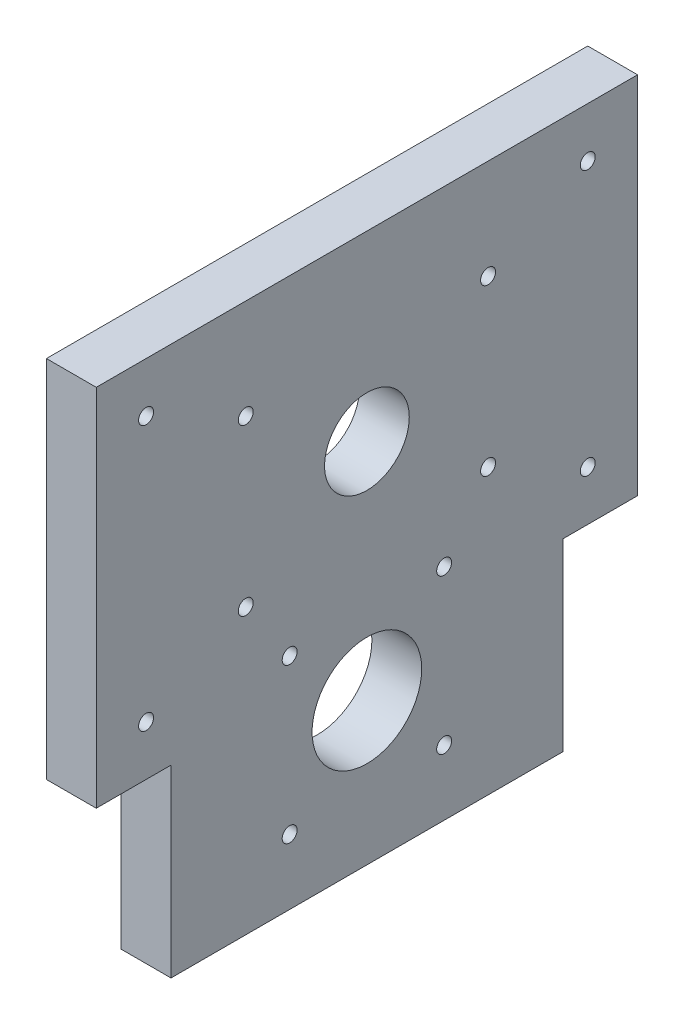
SolidWorks part; units mm, degrees
ref_plane "前视基准面" through (0, 0, 0) normal (0, 0, 1) x (1, 0, 0)
ref_plane "上视基准面" through (0, 0, 0) normal (0, 1, 0) x (1, 0, 0)
ref_plane "右视基准面" through (0, 0, 0) normal (1, 0, 0) x (0, 0, -1)
sketch "草图1" plane through (0, 0, 0) normal (1, 0, 0) x (0, 0, -1)
  line L0 (0, 0) -> (27.5, 0) construction
  line L1 (0, 0) -> (-27.5, 0) construction
  line L2 (-27.5, 0) -> (-27.5, 36.58) construction
  line L3 (0, 0) -> (-27.5, 36.58) construction
  line L4 (0, 0) -> (0, -45) construction
  line L5 (-27.5, 36.58) -> (-27.5, 26.58) construction
  line L6 (-27.5, 26.58) -> (-37.5, 26.58) construction
  line L7 (-27.5, 26.58) -> (-27.5, 16.58) construction
  line L8 (-27.5, 16.58) -> (-17.5, 16.58) construction
  line L9 (-27.5, 36.58) -> (-47.5, 36.58)
  line L10 (21.13, 16.58) -> (31.13, 16.58) [skipped]
  line L11 (-47.5, 36.58) -> (-47.5, -36.58)
  line L12 (22.315, -45) -> (-8.685, -45) construction
  line L14 (-8.685, -45) -> (-8.685, -29.5) construction
  line L15 (-8.685, -45) -> (-8.685, -60.5) construction
  line L16 (22.315, -45) -> (22.315, -29.5) construction
  line L17 (22.315, -45) -> (22.315, -60.5) construction
  line L18 (-47.5, -36.58) -> (-32.5, -36.58)
  line L19 (-32.5, -36.58) -> (-32.5, -73.58)
  line L20 (-32.5, -73.58) -> (46.13, -73.58)
  line L21 (46.13, -73.58) -> (46.13, -36.58)
  line L22 (46.13, -36.58) -> (61.13, -36.58)
  line L23 (61.13, -36.58) -> (61.13, 36.58)
  line L24 (61.13, 36.58) -> (-27.5, 36.58)
  line L25 (-17.5, 16.58) -> (31.13, -16.58) construction
  circle A0 centre (-8.685, -29.5) radius 1.5
  circle A1 centre (-37.5, 26.58) radius 1.5
  circle A2 centre (-17.5, 16.58) radius 1.5
  circle A3 centre (31.13, 16.58) radius 1.5
  circle A4 centre (51.13, 26.58) radius 1.5
  circle A5 centre (-37.5, -26.58) radius 1.5
  circle A6 centre (-17.5, -16.58) radius 1.5
  circle A7 centre (31.13, -16.58) radius 1.5
  circle A8 centre (51.13, -26.58) radius 1.5
  circle A9 centre (22.315, -29.5) radius 1.5
  circle A10 centre (-8.685, -60.5) radius 1.5
  circle A11 centre (22.315, -60.5) radius 1.5
  circle A12 centre (6.815, 0) radius 8.5
  circle A13 centre (6.815, -45) radius 11
  dimension "D7" = 10
  dimension "D8" = 10
  dimension "D10" = 2
  dimension "D1" = 27.5
  dimension "D2" = 27.5
  dimension "D3" = 36.58
  dimension "D4" = 45
  dimension "D5" = 10
  dimension "D6" = 10
  dimension "D12" = 20
  dimension "D13" = 22.315
  dimension "D14" = 8.685
  dimension "D15" = 15.5
  dimension "D16" = 15.5
  dimension "D17" = 15.5
  dimension "D18" = 15.5
  dimension "D19" = 73.16
  dimension "D20" = 15
  dimension "D21" = 15
  dimension "D22" = 88.63
  dimension "D23" = 37
  dimension "D9" = 2
  dimension "D11" = 2
extrude "凸台-拉伸1" add sketch "草图1" along normal blind 10
